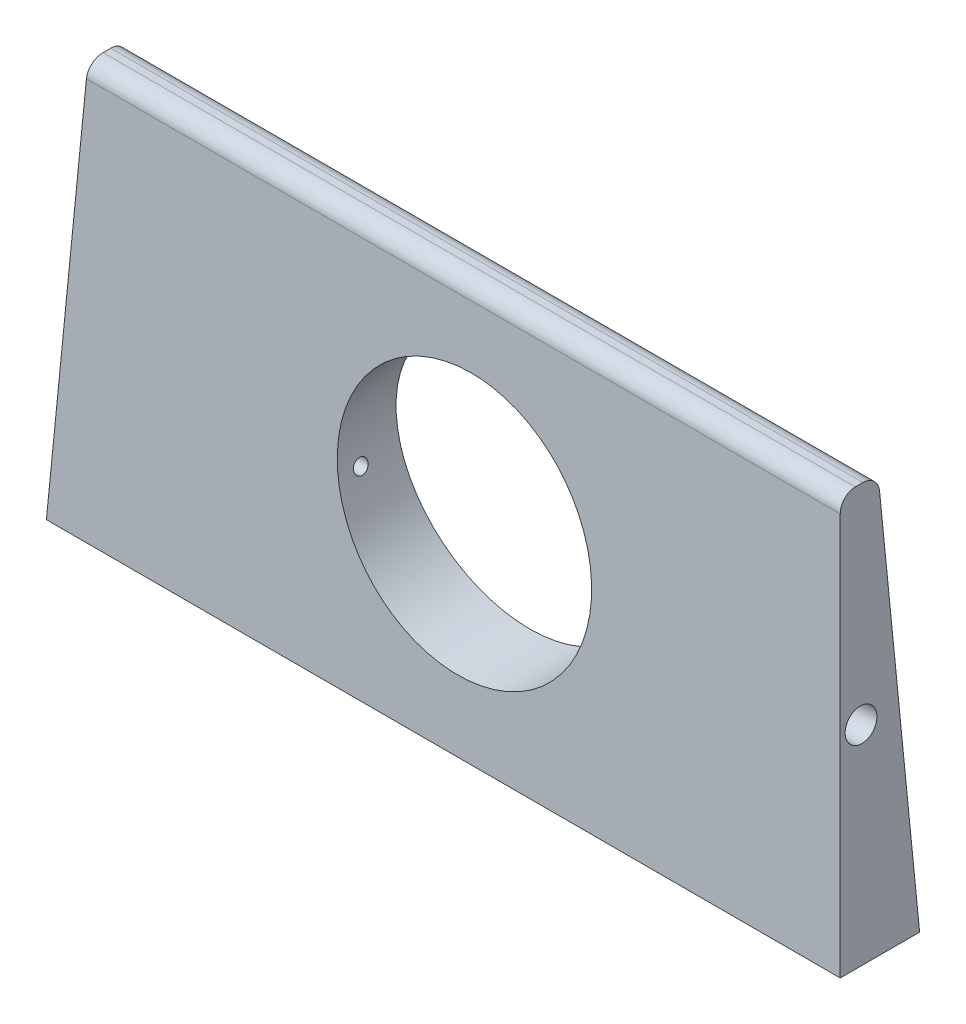
SolidWorks part; units mm, degrees
ref_plane "Front Plane" through (0, 0, 0) normal (0, 0, 1) x (1, 0, 0)
ref_plane "Top Plane" through (0, 0, 0) normal (0, 1, 0) x (1, 0, 0)
ref_plane "Right Plane" through (0, 0, 0) normal (1, 0, 0) x (0, 0, -1)
sketch "Sketch1" plane through (0, 0, 0) normal (0, 1, 0) x (1, 0, 0)
  line L1 (-50, 5) -> (50, 5)
  line L2 (-50, 5) -> (-50, -5)
  line L3 (-50, -5) -> (50, -5)
  line L4 (50, 5) -> (50, -5)
  line L5 (-50, 5) -> (50, -5) construction
  line L6 (-50, -5) -> (50, 5) construction
  point P0 (0, 0)
  dimension "D1" = 100
  dimension "D2" = 10
extrude "Boss-Extrude1" add sketch "Sketch1" along normal blind 50 draft 3
fillet "Fillet1" radius 2 2 edges at (0, 50, -2.3796) (0, 50, 2.3796)
sketch "Sketch2" plane through (0, 0.2613, -4.9863) normal (0, 0.0523, -0.9986) x (-1, 0, 0)
  line L0 (47.4789, 47.909) -> (50, -0.2617) construction
  line L1 (-50, -0.2617) -> (50, -0.2617) construction
  circle A0 centre (-1.3768, 24.7383) radius 16
  dimension "D1" = 50
  dimension "D2" = 25
extrude "Cut-Extrude1" cut sketch "Sketch2" against normal blind 50
sketch "Sketch3" plane through (49.863, 2.6132, 0) normal (0.9986, 0.0523, 0) x (0, 0, -1)
  line L0 (0, 47.4518) -> (-2.1354, -2.6168) construction
  line L1 (-0.4817, 47.4518) -> (0.4817, 47.4518) construction
  line L2 (-5, -2.6168) -> (5, -2.6168) construction
  circle A0 centre (-1.0677, 22.4175) radius 2
  dimension "D1" = 4
extrude "Cut-Extrude2" cut sketch "Sketch3" against normal blind 105 draft 1
